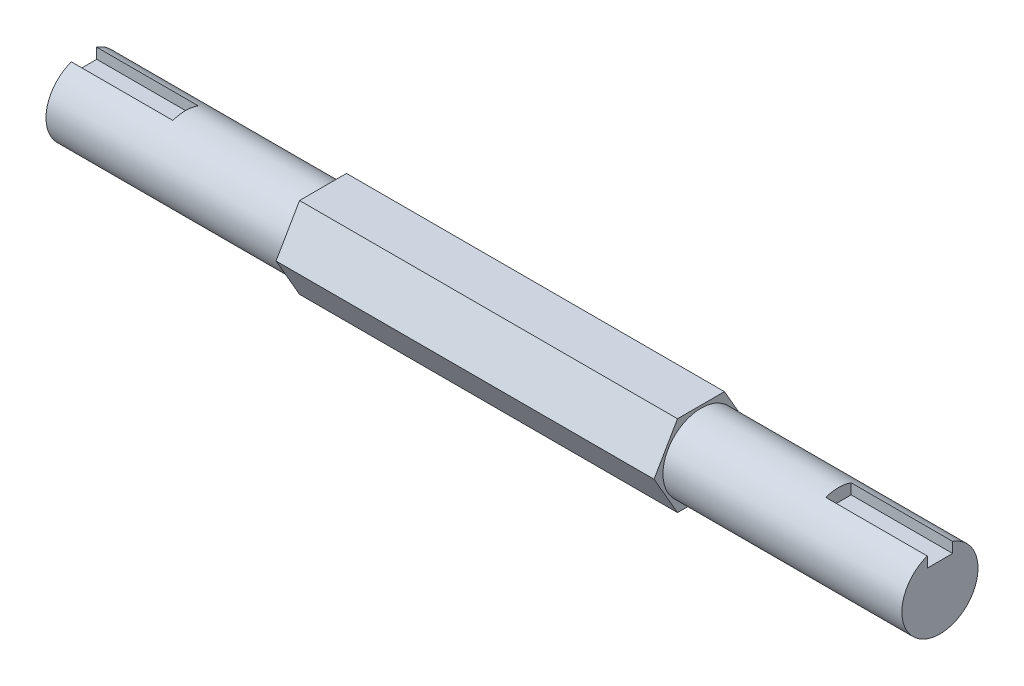
SolidWorks part; units mm, degrees
ref_plane "Front Plane" through (0, 0, 0) normal (0, 0, 1) x (1, 0, 0)
ref_plane "Top Plane" through (0, 0, 0) normal (0, 1, 0) x (1, 0, 0)
ref_plane "Right Plane" through (0, 0, 0) normal (1, 0, 0) x (0, 0, -1)
sketch "Sketch1" plane through (0, 0, 0) normal (1, 0, 0) x (0, 0, -1)
  circle A0 centre (0, 0) radius 15
  dimension "D1" = 30
extrude "Boss-Extrude2" add sketch "Sketch1" along normal mid plane 337.4
sketch "Sketch2" plane through (0, 0, 0) normal (1, 0, 0) x (0, 0, -1)
  line L1 (-18.5041, 0) -> (-9.252, -16.025)
  line L2 (-9.252, -16.025) -> (9.252, -16.025)
  line L3 (9.252, -16.025) -> (18.5041, 0)
  line L4 (18.5041, 0) -> (9.252, 16.025)
  line L5 (9.252, 16.025) -> (-9.252, 16.025)
  line L6 (-9.252, 16.025) -> (-18.5041, 0)
  circle A0 centre (0, 0) radius 16.025 construction
  dimension "D1" = 32.05
extrude "Boss-Extrude3" add sketch "Sketch2" along normal mid plane 149
sketch "Sketch3" plane through (168.7, 0, 0) normal (1, 0, 0) x (0, 0, -1)
  line L0 (0, 17.6275) -> (0, -17.6275) construction
  line L1 (-5, 10) -> (5, 10)
  line L2 (-5, 10) -> (-5, 20)
  line L3 (-5, 20) -> (5, 20)
  line L4 (5, 10) -> (5, 20)
  line L5 (-5, 10) -> (5, 20) construction
  line L6 (-5, 20) -> (5, 10) construction
  circle A3 centre (0, 0) radius 15 construction
  point P0 (0, 15)
  point P7 (0, 0)
  point P9 (0, 0)
  dimension "D1" = 10
  dimension "D2" = 10
extrude "Cut-Extrude1" cut sketch "Sketch3" against normal blind 40
mirror "Mirror1" about plane through (0, 0, 0) normal (1, 0, 0) of "Cut-Extrude1"
sketch "Sketch5" plane through (0, 0, 0) normal (0, 0, 1) x (1, 0, 0)
  line L0 (0, 0) -> (-265.5879, 0) construction
